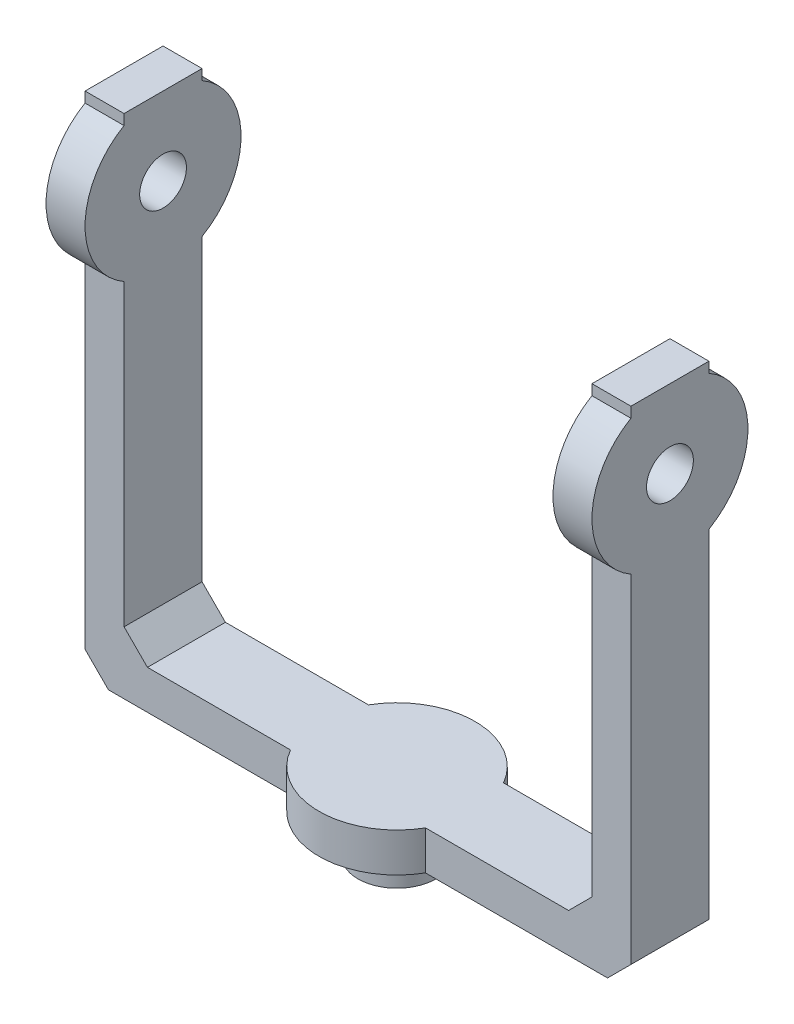
SolidWorks part; units mm, degrees
ref_plane "Front" through (0, 0, 0) normal (0, 0, 1) x (1, 0, 0)
ref_plane "Top" through (0, 0, 0) normal (0, 1, 0) x (1, 0, 0)
ref_plane "Right" through (0, 0, 0) normal (1, 0, 0) x (0, 0, -1)
sketch "Sketch1" plane through (0, 0, 0) normal (0, 1, 0) x (1, 0, 0)
  circle A0 centre (0, 0) radius 250
  dimension "D1" = 500
extrude "Boss-Extrude1" add sketch "Sketch1" along normal blind 250
sketch "Sketch2" plane through (0, 250, 0) normal (0, 1, 0) x (1, 0, 0)
  line L0 (-433.0127, 250) -> (-1500, 250)
  line L1 (0, 0) -> (-1500, 0) construction
  line L2 (1500, 250) -> (433.0127, 250)
  line L3 (1500, 250) -> (1500, -250)
  line L4 (1500, -250) -> (433.0127, -250)
  line L5 (-1500, 250) -> (-1500, -250)
  line L6 (1500, 250) -> (-307.8617, -51.3103) construction
  line L7 (1500, -250) -> (-1500, 250) construction
  line L8 (-433.0127, -250) -> (-1500, -250)
  arc A0 (-433.0127, -250) -> (433.0127, -250) centre (0, 0) ccw
  arc A1 (433.0127, 250) -> (-433.0127, 250) centre (0, 0) ccw
  dimension "D1" = 1000
  dimension "D2" = 500
  dimension "D3" = 3000
extrude "Boss-Extrude2" add sketch "Sketch2" along normal blind 250
ref_plane "Plane1" through (0, 250, 0) normal (0, 1, 0) x (1, 0, 0)
sketch "Sketch4" plane through (0, 250, 0) normal (0, 1, 0) x (1, 0, 0)
  line L1 (1500, 250) -> (1750, 250)
  line L2 (1500, 250) -> (1500, -250)
  line L3 (1500, -250) -> (1750, -250)
  line L4 (1750, 250) -> (1750, -250)
  dimension "D1" = 250
  dimension "D2" = 500
extrude "Boss-Extrude3" add sketch "Sketch4" along normal blind 3250
ref_plane "Plane2" through (1500, 0, 0) normal (-1, 0, 0) x (0, 0, 1)
sketch "Sketch7" plane through (1500, 0, 0) normal (-1, 0, 0) x (0, 0, 1)
  line L0 (250, 3500) -> (-250, 3500) construction
  circle A0 centre (0, 3000) radius 500
  dimension "D1" = 1000
  dimension "D2" = 500
extrude "Boss-Extrude4" add sketch "Sketch7" against normal blind 250
sketch "Sketch8" plane through (1500, 0, 0) normal (-1, 0, 0) x (0, 0, 1)
  circle A0 centre (0, 3000) radius 150
extrude "Cut-Extrude1" cut sketch "Sketch8" against normal blind 250
mirror "Mirror1" about plane through (0, 0, 0) normal (1, 0, 0) of "Boss-Extrude3", "Boss-Extrude4", "Cut-Extrude1"
chamfer "Chamfer1" distance 150 angle 45 4 edges at (1750, 250, 0) (1500, 500, 0) (-1750, 250, 0) (-1500, 500, 0)
equation "\"BaseDiameter\" = .5"
equation "\"D1@Sketch1\"=\"BaseDiameter\""
equation "\"BaseHeight\"=0.25"
equation "\"D1@Boss-Extrude1\"=\"BaseHeight\""
equation "\"topdiameter\"=1"
equation "\"D1@Sketch2\"=\"topdiameter\""
equation "\"topheight\"=0.25"
equation "\"D1@Boss-Extrude2\"=\"topheight\""
